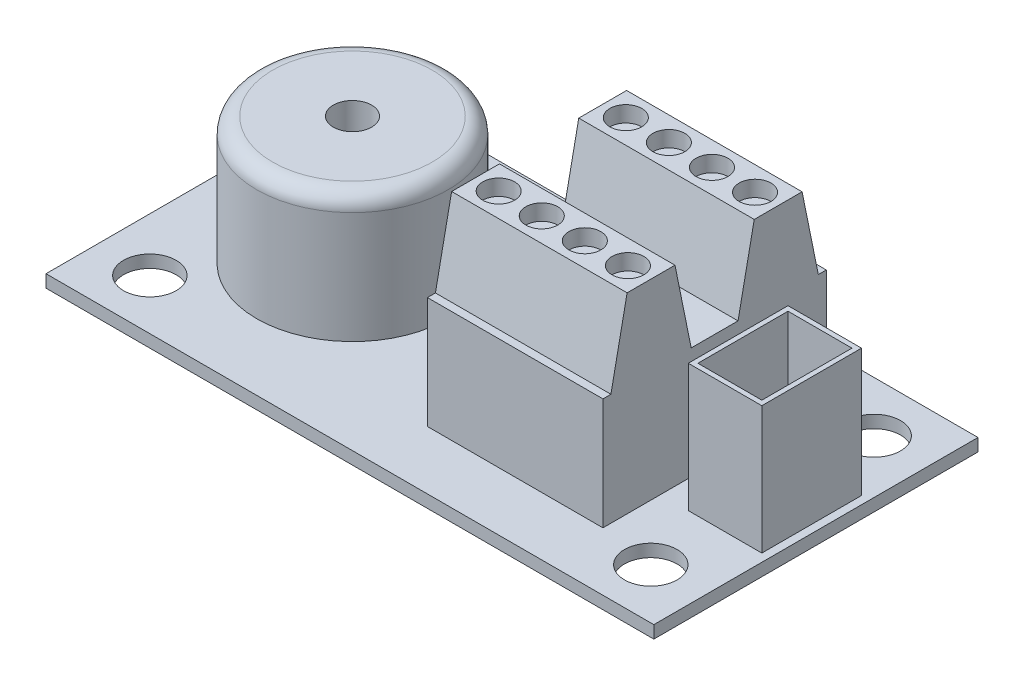
SolidWorks part; units mm, degrees
ref_plane "Front Plane" through (0, 0, 0) normal (0, 0, 1) x (1, 0, 0)
ref_plane "Top Plane" through (0, 0, 0) normal (0, 1, 0) x (1, 0, 0)
ref_plane "Right Plane" through (0, 0, 0) normal (1, 0, 0) x (0, 0, -1)
sketch "Sketch1" plane through (0, 0, 0) normal (0, 1, 0) x (1, 0, 0)
  line L1 (-19.05, 10.16) -> (19.05, 10.16)
  line L2 (-19.05, 10.16) -> (-19.05, -10.16)
  line L3 (-19.05, -10.16) -> (19.05, -10.16)
  line L4 (19.05, 10.16) -> (19.05, -10.16)
  dimension "D1" = 38.1
  dimension "D2" = 20.32
  dimension "D3" = 19.05
  dimension "D4" = 10.16
extrude "Boss-Extrude1" add sketch "Sketch1" along normal blind 0.7874
sketch "Sketch3" plane through (0, 0, 0) normal (0, -1, 0) x (1, 0, 0)
  line L0 (-19.4735, 0.2786) -> (21.4635, 0.2786) construction
  circle A0 centre (-15.7, 7) radius 1.65
  circle A1 centre (15.7, 7) radius 1.65
  circle A2 centre (15.7, -7) radius 1.65
  circle A3 centre (-15.7, -7) radius 1.65
  dimension "D3" = 3.3
  dimension "D1" = 15.7
  dimension "D2" = 7
  dimension "D4" = 2
  dimension "D5" = 2
extrude "Cut-Extrude2" cut sketch "Sketch3" against normal blind 10
sketch "Sketch4" plane through (0, 0.7874, 0) normal (0, 1, 0) x (1, 0, 0)
  circle A0 centre (-10, 0) radius 6
  dimension "D1" = 12
  dimension "D2" = 10
extrude "Boss-Extrude2" add sketch "Sketch4" along normal blind 8
fillet "Fillet1" radius 1 1 edges at (-10, 8.7874, 6)
sketch "Sketch5" plane through (0, 8.7874, 0) normal (0, 1, 0) x (1, 0, 0)
  circle A0 centre (-10, 0) radius 1.2
  dimension "D1" = 2.4
extrude "Cut-Extrude3" cut sketch "Sketch5" against normal blind 2
sketch "Sketch6" plane through (0, 0.7874, 0) normal (0, 1, 0) x (1, 0, 0)
  line L1 (12.2, -6.5) -> (1.2, -6.5)
  line L2 (12.2, -6.5) -> (12.2, 7.5)
  line L3 (12.2, 7.5) -> (1.2, 7.5)
  line L4 (1.2, -6.5) -> (1.2, 7.5)
  dimension "D1" = 11
  dimension "D2" = 14
  dimension "D3" = 7.5
  dimension "D4" = 1.2
extrude "Boss-Extrude3" add sketch "Sketch6" along normal blind 12
sketch "Sketch7" plane through (12.2, 0, 0) normal (1, 0, 0) x (0, 0, -1)
  line L0 (-6, 7.7874) -> (-4.9842, 12.7874)
  line L2 (-6.5, 12.7874) -> (7.5, 12.7874) construction
  line L3 (-4.9842, 12.7874) -> (-1.9842, 12.7874) construction
  line L4 (-1.9842, 12.7874) -> (-0.9683, 7.7874)
  line L5 (-0.9683, 7.7874) -> (1.9683, 7.7874)
  line L6 (1.9683, 7.7874) -> (2.9842, 12.7874)
  line L7 (2.9842, 12.7874) -> (5.9842, 12.7874) construction
  line L8 (5.9842, 12.7874) -> (7, 7.7874)
  line L9 (7, 7.7874) -> (7.5, 7.7874)
  line L10 (7.5, 12.7874) -> (7.5, 0.7874) construction
  line L11 (-6, 7.7874) -> (-6.5, 7.7874)
  line L12 (-6.5, 12.7874) -> (-6.5, 0.7874) construction
  line L13 (-6.5, 7.7874) -> (-6.5, 12.7874)
  line L14 (-6.5, 12.7874) -> (-4.9842, 12.7874)
  line L15 (-1.9842, 12.7874) -> (2.9842, 12.7874)
  line L16 (5.9842, 12.7874) -> (7.5, 12.7874)
  line L17 (7.5, 12.7874) -> (7.5, 7.7874)
  line L18 (-3.4842, 12.7874) -> (-3.4842, 0.7874) construction
  line L19 (-6.5, 0.7874) -> (7.5, 0.7874) construction
  line L20 (4.4842, 12.7874) -> (4.4842, 0.7874) construction
  line L21 (0.5, 7.7874) -> (0.5, 0.7874) construction
  line L22 (-3.4842, 4.6649) -> (0.5, 4.6649) construction
  line L23 (0.5, 4.6649) -> (4.4842, 4.6649) construction
  point P30 (1.8121, 12.7874)
  point P31 (5.8977, 7.859)
  point P34 (-0.7704, 7.4392)
  point P35 (0, 0)
  point P36 (0.5, 0.7874)
  point P37 (-6.7781, 7.7874)
  point P38 (-5.9381, 7.7874)
  dimension "D1" = 3
  dimension "D2" = 3
  dimension "D3" = 1.5
  dimension "D4" = 1.5
  dimension "D5" = 5
  dimension "D6" = 0.5
extrude "Cut-Extrude4" cut sketch "Sketch7" against normal blind 12
sketch "Sketch8" plane through (0, 12.7874, 0) normal (0, 1, 0) x (1, 0, 0)
  line L0 (21.2567, 1.9721) -> (-25.1218, 1.9721) construction
  line L1 (12.2, -3.4842) -> (1.2, -3.4842) construction
  line L2 (12.2, -4.9842) -> (12.2, -1.9842) construction
  line L3 (1.2, -1.9842) -> (1.2, -4.9842) construction
  line L4 (6.7, -4.9842) -> (6.7, -1.9842) construction
  line L5 (12.2, 4.4842) -> (1.2, 4.4842) construction
  line L6 (12.2, -4.9842) -> (1.2, -4.9842) construction
  line L7 (1.2, -1.9842) -> (12.2, -1.9842) construction
  line L8 (6.7, 2.9842) -> (6.7, 5.9842) construction
  circle A0 centre (10.75, -3.4842) radius 1
  circle A1 centre (8.05, -3.4842) radius 1
  circle A2 centre (5.35, -3.4842) radius 1
  circle A3 centre (2.65, -3.4842) radius 1
  circle A4 centre (10.75, 4.4842) radius 1
  circle A5 centre (8.05, 4.4842) radius 1
  circle A6 centre (5.35, 4.4842) radius 1
  circle A7 centre (2.65, 4.4842) radius 1
  dimension "D1" = 2
  dimension "D5" = 2
  dimension "D3" = 1.35
  dimension "D4" = 1.35
  dimension "D6" = 1.35
  dimension "D7" = 1.35
  dimension "D2" = 4
extrude "Cut-Extrude5" cut sketch "Sketch8" against normal blind 1
sketch "Sketch9" plane through (0, 0.7874, 0) normal (0, 1, 0) x (1, 0, 0)
  line L0 (18.2505, -2.59) -> (18.2505, 3.0586)
  line L1 (18.5505, -2.89) -> (13.9422, -2.89)
  line L2 (18.5505, -2.89) -> (18.5505, 3.3586)
  line L3 (18.5505, 3.3586) -> (13.9422, 3.3586)
  line L4 (13.9422, -2.89) -> (13.9422, 3.3586)
  line L5 (18.2505, 3.0586) -> (14.2422, 3.0586)
  line L6 (14.2422, -2.59) -> (14.2422, 3.0586)
  line L7 (18.2505, -2.59) -> (14.2422, -2.59)
  dimension "D1" = 0.3
extrude "Boss-Extrude4" add sketch "Sketch9" along normal blind 8
